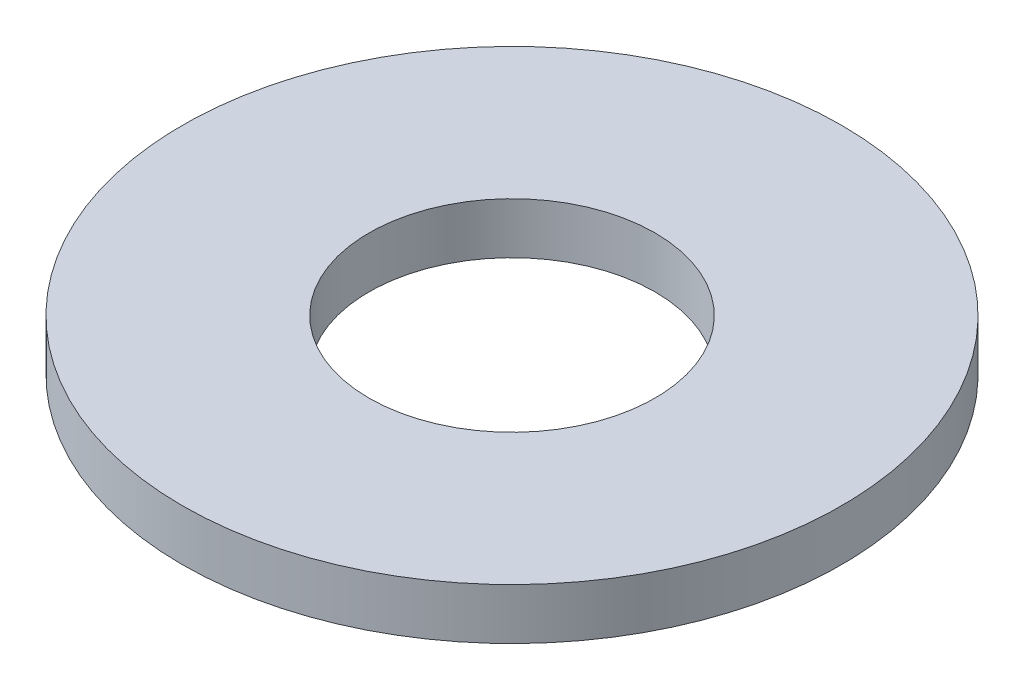
SolidWorks part; units mm, degrees
ref_plane "Front Plane" through (0, 0, 0) normal (0, 0, 1) x (1, 0, 0)
ref_plane "Top Plane" through (0, 0, 0) normal (0, 1, 0) x (1, 0, 0)
ref_plane "Right Plane" through (0, 0, 0) normal (1, 0, 0) x (0, 0, -1)
sketch "Sketch1" plane through (0, 0, 0) normal (0, 1, 0) x (1, 0, 0)
  circle A0 centre (0, 0) radius 6.45
  circle A1 centre (0, 0) radius 2.8
  dimension "D1" = 12.9
  dimension "D2" = 5.6
extrude "Boss-Extrude1" add sketch "Sketch1" along normal blind 1
